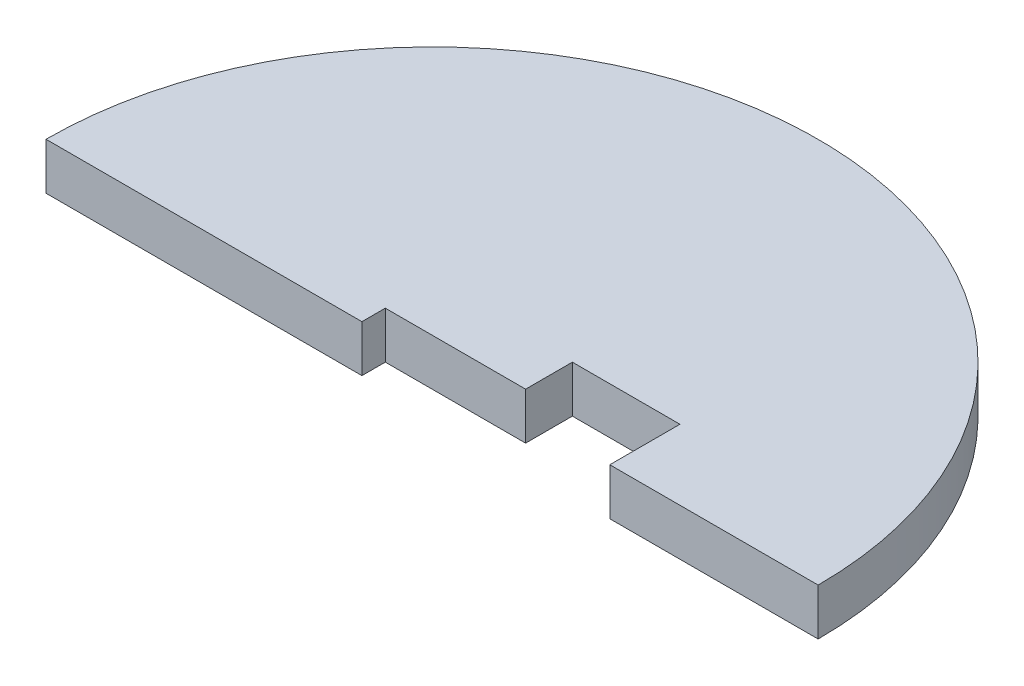
SolidWorks part; units mm, degrees
ref_plane "Front Plane" through (0, 0, 0) normal (0, 0, 1) x (1, 0, 0)
ref_plane "Top Plane" through (0, 0, 0) normal (0, 1, 0) x (1, 0, 0)
ref_plane "Right Plane" through (0, 0, 0) normal (1, 0, 0) x (0, 0, -1)
sketch "Sketch1" plane through (0, 0, 0) normal (0, 1, 0) x (1, 0, 0)
  circle A0 centre (0, 0) radius 82.55
  dimension "D1" = 165.1
extrude "Boss-Extrude1" add sketch "Sketch1" along normal blind 10
sketch "Sketch3" plane through (0, 10, 0) normal (0, 1, 0) x (1, 0, 0)
  line L0 (-82.55, 0) -> (82.55, 0)
  circle A0 centre (0, 0) radius 82.55 construction
  arc A1 (82.55, 0) -> (-82.55, 0) centre (0, 0) ccw
extrude "Cut-Extrude2" cut sketch "Sketch3" against normal blind 10 flip side to cut
extrude "Cut-Extrude3" cut sketch "Sketch4" against normal blind 13
sketch "Sketch4" plane through (0, 13, 0) normal (0, 1, 0) x (1, 0, 0)
  line L1 (-15, 5) -> (15, 5)
  line L2 (-15, 5) -> (-15, -5)
  line L3 (-15, -5) -> (15, -5)
  line L4 (15, 5) -> (15, -5)
  line L5 (-15, 5) -> (15, -5) construction
  line L6 (-15, -5) -> (15, 5) construction
  point P0 (0, 0)
extrude "Cut-Extrude5" cut sketch "Sketch6" against normal blind 10
sketch "Sketch6" plane through (0, 10, 0) normal (0, 1, 0) x (1, 0, 0)
  line L0 (15, 0) -> (0, 0) construction
  line L1 (15, 15) -> (38, 15)
  line L2 (15, 15) -> (15, -15)
  line L3 (15, -15) -> (38, -15)
  line L4 (38, 15) -> (38, -15)
